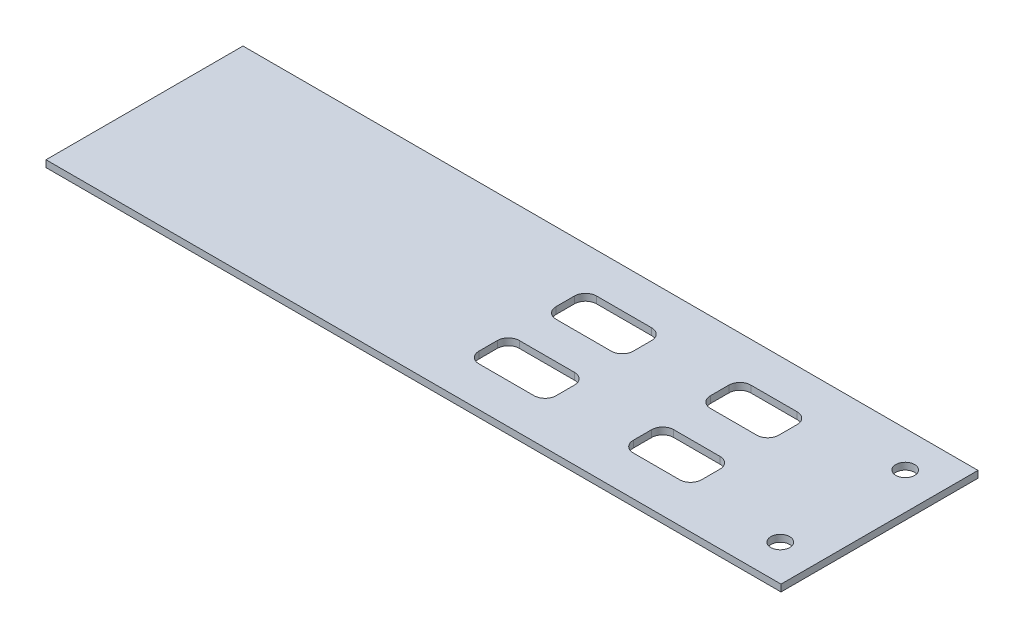
SolidWorks part; units mm, degrees
ref_plane "Front Plane" through (0, 0, 0) normal (0, 0, 1) x (1, 0, 0)
ref_plane "Top Plane" through (0, 0, 0) normal (0, 1, 0) x (1, 0, 0)
ref_plane "Right Plane" through (0, 0, 0) normal (1, 0, 0) x (0, 0, -1)
sketch "Sketch1" plane through (0, 0, 0) normal (0, 1, 0) x (1, 0, 0)
  line L1 (0, 0) -> (152.4, 0)
  line L2 (0, 0) -> (0, 68.072)
  line L3 (0, 68.072) -> (152.4, 68.072)
  line L4 (152.4, 0) -> (152.4, 68.072)
  dimension "D1" = 68.072
  dimension "D2" = 152.4
extrude "Boss-Extrude1" add sketch "Sketch1" along normal blind 2.3622
sketch "Sketch2" plane through (0, 2.3622, 0) normal (0, 1, 0) x (1, 0, 0)
  line L0 (0, 68.072) -> (0, 0) construction
  line L1 (30.48, 54.356) -> (57.15, 54.356)
  line L2 (30.48, 54.356) -> (30.48, 40.386)
  line L3 (30.48, 40.386) -> (57.15, 40.386)
  line L4 (57.15, 54.356) -> (57.15, 40.386)
  line L5 (83.82, 54.356) -> (107.442, 54.356)
  line L6 (83.82, 54.356) -> (83.82, 40.386)
  line L7 (83.82, 40.386) -> (107.442, 40.386)
  line L8 (107.442, 54.356) -> (107.442, 40.386)
  line L9 (152.4, 0) -> (152.4, 68.072) construction
  line L10 (30.48, 27.686) -> (57.15, 27.686)
  line L11 (30.48, 27.686) -> (30.48, 13.716)
  line L12 (30.48, 13.716) -> (57.15, 13.716)
  line L13 (57.15, 27.686) -> (57.15, 13.716)
  line L14 (83.82, 27.686) -> (107.442, 27.686)
  line L15 (83.82, 27.686) -> (83.82, 13.716)
  line L16 (83.82, 13.716) -> (107.442, 13.716)
  line L17 (107.442, 27.686) -> (107.442, 13.716)
  point P10 (83.82, 47.371)
  point P17 (0, 34.036)
  dimension "D1" = 26.67
  dimension "D2" = 23.622
  dimension "D3" = 44.958
  dimension "D4" = 13.97
  dimension "D5" = 12.7
  dimension "D6" = 6.35
  dimension "D7" = 30.48
extrude "Cut-Extrude1" cut sketch "Sketch2" against normal through all
fillet "Fillet1" radius 3.81 16 edges at (83.82, 1.1811, -13.716) (83.82, 1.1811, -40.386) (30.48, 1.1811, -40.386) (30.48, 1.1811, -13.716) (107.442, 1.1811, -13.716) (57.15, 1.1811, -40.386) (57.15, 1.1811, -13.716) (107.442, 1.1811, -40.386) (107.442, 1.1811, -27.686) (107.442, 1.1811, -54.356) (57.15, 1.1811, -27.686) (57.15, 1.1811, -54.356) (30.48, 1.1811, -27.686) (83.82, 1.1811, -27.686) (83.82, 1.1811, -54.356) (30.48, 1.1811, -54.356)
sketch "Sketch4" plane through (0, 0, 0) normal (-1, 0, 0) x (0, 0, 1)
  line L1 (-68.072, 2.3622) -> (0, 2.3622)
  line L2 (-68.072, 2.3622) -> (-68.072, 0)
  line L3 (-68.072, 0) -> (0, 0)
  line L4 (0, 2.3622) -> (0, 0)
extrude "Boss-Extrude2" add sketch "Sketch4" along normal blind 101.6
sketch "Sketch5" plane through (0, 0, 0) normal (0, -1, 0) x (1, 0, 0)
  line L0 (152.4, 0) -> (152.4, -68.072) construction
  line L3 (139.7, -12.446) -> (139.7, -55.626) construction
  circle A0 centre (139.7, -12.446) radius 3.2639
  circle A1 centre (139.7, -55.626) radius 3.2639
  point P6 (139.7, -34.036)
  point P7 (152.4, -34.036)
  dimension "D1" = 6.5278
  dimension "D2" = 12.7
  dimension "D3" = 43.18
extrude "Cut-Extrude2" cut sketch "Sketch5" against normal through all
